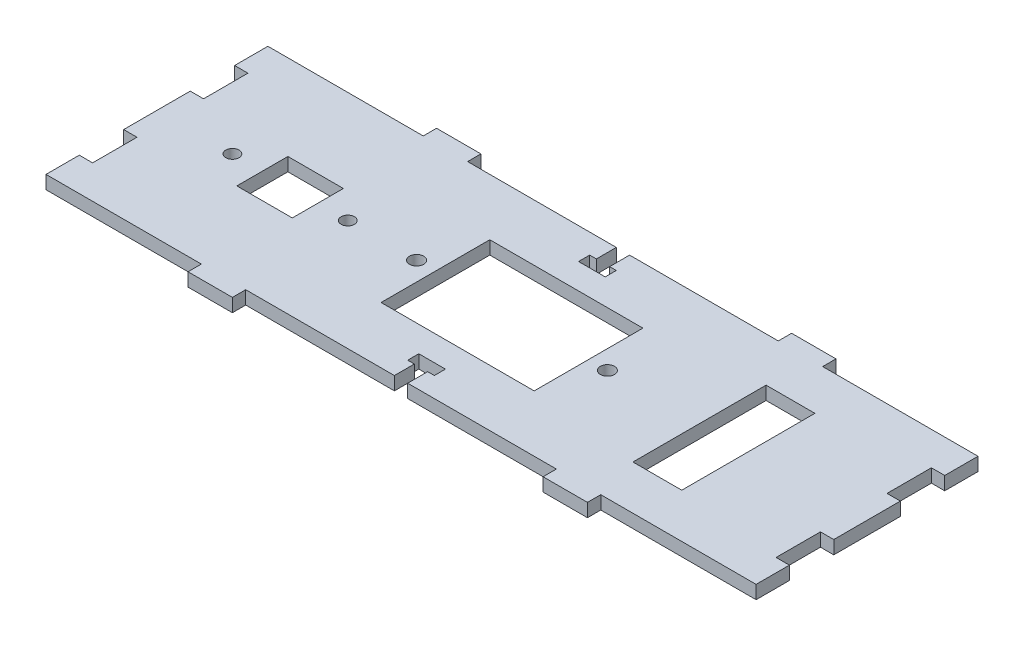
SolidWorks part; units mm, degrees
ref_plane "Front Plane" through (0, 0, 0) normal (0, 0, 1) x (1, 0, 0)
ref_plane "Top Plane" through (0, 0, 0) normal (0, 1, 0) x (1, 0, 0)
ref_plane "Right Plane" through (0, 0, 0) normal (1, 0, 0) x (0, 0, -1)
sketch "Sketch3" plane through (0, 0, 0) normal (0, 1, 0) x (1, 0, 0)
  line L0 (0, 66.6216) -> (0, -68.7838) construction
  line L1 (-104.3243, 0) -> (111.6216, 0) construction
  line L3 (-80, 28) -> (80, 28)
  line L4 (-80, 28) -> (-80, -28)
  line L5 (-80, -28) -> (80, -28)
  line L6 (80, 28) -> (80, -28)
  line L7 (-80, 28) -> (80, -28) construction
  line L8 (-80, -28) -> (80, 28) construction
  point P1 (0, 0)
  dimension "D1" = 56
  dimension "D2" = 160
extrude "Boss-Extrude1" add sketch "Sketch3" along normal blind 3
sketch "Sketch4" plane through (0, 3, 0) normal (0, 1, 0) x (1, 0, 0)
  line L0 (0, 16.1567) -> (0, -10.6496) construction
  line L1 (-38.2504, 0) -> (41.6071, 0) construction
  line L2 (-80, 28) -> (-80, -28) construction
  line L3 (-80, 17.5) -> (-77, 17.5)
  line L4 (-80, 17.5) -> (-80, 7.5)
  line L5 (-80, 7.5) -> (-77, 7.5)
  line L6 (-77, 17.5) -> (-77, 7.5)
  line L7 (-35, 28) -> (-35, 25)
  line L8 (-80, 28) -> (-45, 28)
  line L9 (-80, 28) -> (-80, 25)
  line L10 (-80, 25) -> (-45, 25)
  line L11 (-45, 28) -> (-45, 25)
  line L12 (80, 28) -> (-80, 28) construction
  line L13 (-35, 25) -> (-1.5, 25)
  line L14 (-1.5, 25) -> (-1.5, 20.5)
  line L15 (-1.5, 20.5) -> (-3, 20.5)
  line L16 (-3, 20.5) -> (-3, 18)
  line L17 (-3, 18) -> (3, 18)
  line L18 (3, 18) -> (3, 20.5)
  line L19 (3, 20.5) -> (1.5, 20.5)
  line L20 (1.5, 20.5) -> (1.5, 25)
  line L21 (1.5, 25) -> (35, 25)
  line L22 (35, 25) -> (35, 28)
  line L23 (35, 28) -> (-35, 28)
  line L24 (45, 28) -> (45, 25)
  line L25 (80, 25) -> (45, 25)
  line L26 (80, 28) -> (80, 25)
  line L27 (80, 28) -> (45, 28)
  line L28 (77, 17.5) -> (77, 7.5)
  line L29 (80, 7.5) -> (77, 7.5)
  line L30 (80, 17.5) -> (80, 7.5)
  line L31 (80, 17.5) -> (77, 17.5)
  line L32 (80, -17.5) -> (77, -17.5)
  line L33 (80, -17.5) -> (80, -7.5)
  line L34 (80, -7.5) -> (77, -7.5)
  line L35 (77, -17.5) -> (77, -7.5)
  line L36 (80, -28) -> (45, -28)
  line L37 (80, -28) -> (80, -25)
  line L38 (80, -25) -> (45, -25)
  line L39 (45, -28) -> (45, -25)
  line L40 (35, -28) -> (-35, -28)
  line L41 (35, -25) -> (35, -28)
  line L42 (1.5, -25) -> (35, -25)
  line L43 (1.5, -20.5) -> (1.5, -25)
  line L44 (3, -20.5) -> (1.5, -20.5)
  line L45 (3, -18) -> (3, -20.5)
  line L46 (-3, -18) -> (3, -18)
  line L47 (-3, -20.5) -> (-3, -18)
  line L48 (-1.5, -20.5) -> (-3, -20.5)
  line L49 (-1.5, -25) -> (-1.5, -20.5)
  line L50 (-35, -25) -> (-1.5, -25)
  line L51 (-45, -28) -> (-45, -25)
  line L52 (-80, -25) -> (-45, -25)
  line L53 (-80, -28) -> (-80, -25)
  line L54 (-80, -28) -> (-45, -28)
  line L55 (-35, -28) -> (-35, -25)
  line L56 (-77, -17.5) -> (-77, -7.5)
  line L57 (-80, -7.5) -> (-77, -7.5)
  line L58 (-80, -17.5) -> (-80, -7.5)
  line L59 (-80, -17.5) -> (-77, -17.5)
  dimension "D1" = 10
  dimension "D2" = 7.5
  dimension "D3" = 3
  dimension "D4" = 3
  dimension "D5" = 45
  dimension "D6" = 35
  dimension "D7" = 35
  dimension "D8" = 3
  dimension "D9" = 3
  dimension "D10" = 10
  dimension "D11" = 2.5
  dimension "D12" = 2.5
  dimension "D13" = 1.5
  dimension "D14" = 1.5
  dimension "D15" = 3
  dimension "D16" = 1.5
extrude "Cut-Extrude1" cut sketch "Sketch4" against normal through all
sketch "Sketch5" plane through (0, 3, 0) normal (0, 1, 0) x (1, 0, 0)
  line L0 (95.955, 0) -> (-17.113, 0) construction
  line L1 (0, 55.7191) -> (0, -40.0322) construction
  line L2 (-50, 49.4036) -> (-50, -41.0508) construction
  line L3 (-17.25, 12.25) -> (17.25, 12.25)
  line L4 (-17.25, 12.25) -> (-17.25, -12.25)
  line L5 (-17.25, -12.25) -> (17.25, -12.25)
  line L6 (17.25, 12.25) -> (17.25, -12.25)
  line L7 (-17.25, 12.25) -> (17.25, -12.25) construction
  line L8 (-17.25, -12.25) -> (17.25, 12.25) construction
  line L9 (42.25, -15) -> (53.25, -15)
  line L10 (42.25, -15) -> (42.25, 15)
  line L11 (42.25, 15) -> (53.25, 15)
  line L12 (53.25, -15) -> (53.25, 15)
  line L13 (42.25, -15) -> (53.25, 15) construction
  line L14 (42.25, 15) -> (53.25, -15) construction
  line L15 (-56.25, 5.75) -> (-43.75, 5.75)
  line L16 (-56.25, 5.75) -> (-56.25, -5.75)
  line L17 (-56.25, -5.75) -> (-43.75, -5.75)
  line L18 (-43.75, 5.75) -> (-43.75, -5.75)
  line L19 (-56.25, 5.75) -> (-43.75, -5.75) construction
  line L20 (-56.25, -5.75) -> (-43.75, 5.75) construction
  circle A0 centre (-21.5, 0) radius 1.6
  circle A1 centre (21.5, 0) radius 1.6
  circle A2 centre (-63, 0) radius 1.5
  circle A3 centre (-37, 0) radius 1.5
  point P1 (0, 0)
  point P14 (47.75, 0)
  point P19 (-50, 0)
  dimension "D3" = 3.2
  dimension "D10" = 3
  dimension "D1" = 34.5
  dimension "D2" = 24.5
  dimension "D4" = 21.5
  dimension "D5" = 30
  dimension "D6" = 11
  dimension "D7" = 25
  dimension "D8" = 11.5
  dimension "D9" = 12.5
  dimension "D11" = 13
  dimension "D12" = 50
extrude "Cut-Extrude2" cut sketch "Sketch5" against normal through all
